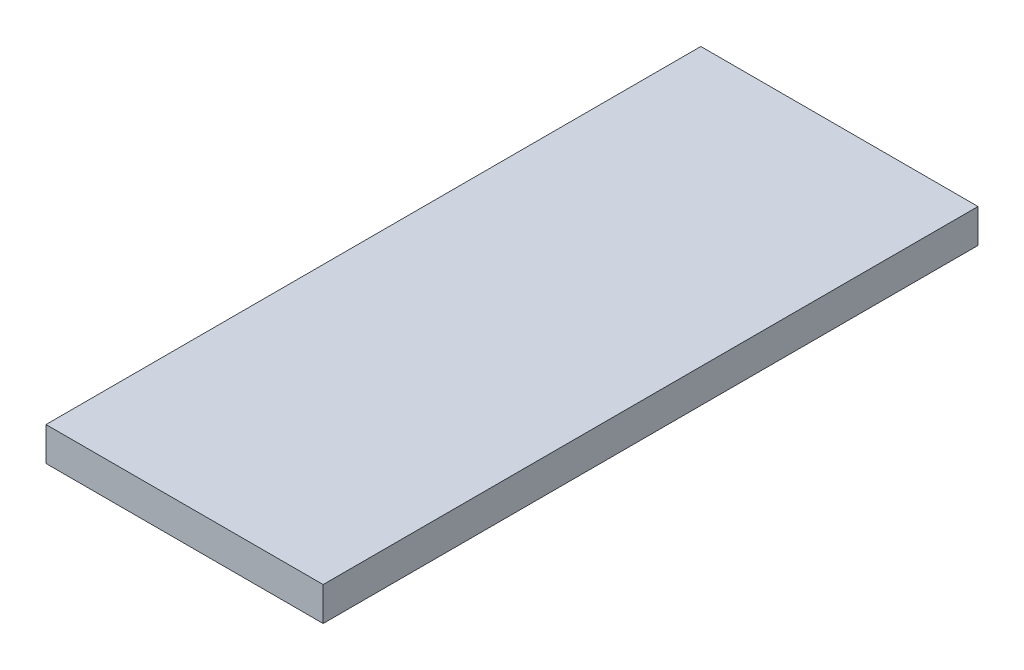
SolidWorks part; units mm, degrees
ref_plane "Front Plane" through (0, 0, 0) normal (0, 0, 1) x (1, 0, 0)
ref_plane "Top Plane" through (0, 0, 0) normal (0, 1, 0) x (1, 0, 0)
ref_plane "Right Plane" through (0, 0, 0) normal (1, 0, 0) x (0, 0, -1)
sketch "Sketch1" plane through (0, 0, 0) normal (0, 0, 1) x (1, 0, 0)
  line L1 (1230, -230) -> (3050, -230)
  line L2 (1230, -230) -> (1230, -8.2988)
  line L3 (1230, -8.2988) -> (3050, -8.2988)
  line L4 (3050, -230) -> (3050, -8.2988)
extrude "Boss-Extrude1" add sketch "Sketch1" along normal blind 4300 from offset 2150
